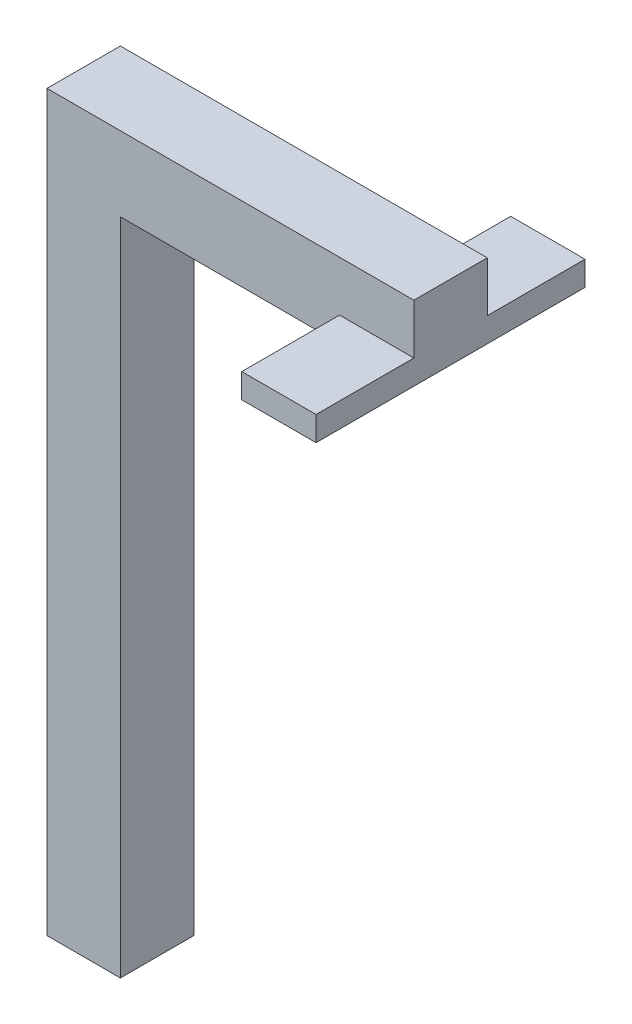
SolidWorks part; units mm, degrees
ref_plane "Front Plane" through (0, 0, 0) normal (0, 0, 1) x (1, 0, 0)
ref_plane "Top Plane" through (0, 0, 0) normal (0, 1, 0) x (1, 0, 0)
ref_plane "Right Plane" through (0, 0, 0) normal (1, 0, 0) x (0, 0, -1)
sketch "Sketch1" plane through (0, 0, 0) normal (0, 0, 1) x (1, 0, 0)
  line L0 (0, 0) -> (7.62, 0)
  line L1 (7.62, 0) -> (7.62, 76.2)
  line L2 (7.62, 76.2) -> (0, 76.2)
  line L3 (0, 76.2) -> (0, 0)
  dimension "D1" = 76.2
  dimension "D2" = 7.62
extrude "Boss-Extrude1" add sketch "Sketch1" along normal blind 7.62
sketch "Sketch3" plane through (7.62, 0, 0) normal (1, 0, 0) x (0, 0, -1)
  line L0 (0, 76.2) -> (0, 68.4598)
  line L1 (0, 0) -> (0, 76.2) construction
  line L2 (0, 68.4598) -> (-7.62, 68.4598)
  line L3 (-7.62, 0) -> (-7.62, 76.2) construction
  line L4 (-7.62, 68.4598) -> (-7.62, 76.2)
  line L5 (-7.62, 76.2) -> (0, 76.2)
extrude "Boss-Extrude3" add sketch "Sketch3" along normal blind 30.48
sketch "Sketch6" plane through (0, 68.4598, 0) normal (0, -1, 0) x (-1, 0, 0)
  line L0 (-38.1, -7.62) -> (-38.1, -17.78)
  line L9 (-38.1, 10.1507) -> (-38.1, 0)
  line L10 (-38.1, 10.1507) -> (-30.3826, 10.1507)
  line L11 (-38.1, -7.62) -> (-38.1, 0)
  line L12 (-30.3826, 10.1507) -> (-30.3826, -17.78)
  line L13 (-30.3826, -17.78) -> (-38.1, -17.78)
  line L14 (-38.1, -7.62) -> (0, -7.62) construction
  point P3 (0, 0)
  dimension "D1" = 27.9307
  dimension "D2" = 7.7174
  dimension "D3" = 10.16
extrude "Boss-Extrude4" add sketch "Sketch6" against normal blind 2.54
